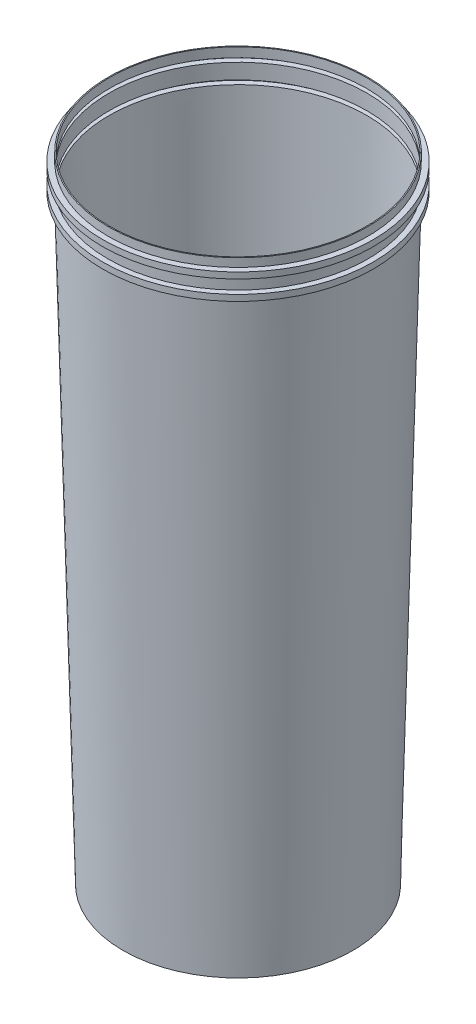
SolidWorks part; units mm, degrees
material "PVC Rigid"
ref_plane "Front Plane" through (0, 0, 0) normal (0, 0, 1) x (1, 0, 0)
ref_plane "Top Plane" through (0, 0, 0) normal (0, 1, 0) x (1, 0, 0)
ref_plane "Right Plane" through (0, 0, 0) normal (1, 0, 0) x (0, 0, -1)
sketch "Sketch1" plane through (0, 0, 0) normal (0, 0, 1) x (1, 0, 0)
  line L0 (0, 620) -> (-126, 620)
  line L11 (0, 0) -> (0, 620)
  line L12 (-126, 620) -> (-126, 610.7636)
  line L13 (-126, 610.7636) -> (-131.4225, 610.7636)
  line L14 (-131.4225, 610.7636) -> (-131.4225, 606.7636)
  line L15 (-131.4225, 606.7636) -> (-126.2576, 606.7636)
  line L16 (-126.2576, 606.7636) -> (-126.2576, 591.7636)
  line L17 (-126.2576, 591.7636) -> (-131.4225, 591.7636)
  line L18 (-131.4225, 591.7636) -> (-131.4225, 587.7636)
  line L19 (-131.4225, 587.7636) -> (-126.2576, 587.7636)
  line L20 (-126.2576, 587.7636) -> (-111.6099, 0)
  line L21 (-111.6099, 0) -> (0, 0)
  dimension "D6" = 620
revolve "Revolve1" add sketch "Sketch1" angle 360 about L11
shell "Shell4" [suppressed] thickness 1
shell "Shell5" thickness 1
sketch "Sketch2" [suppressed] plane through (0, 621, 0) normal (0, 1, 0) x (1, 0, 0)
  circle A0 centre (78.2296, 0) radius 15
  dimension "D1" = 30
extrude "Cut-Extrude1" [suppressed] cut sketch "Sketch2" against normal up to next
sketch "Sketch3" [suppressed] plane through (0, 621, 0) normal (0, 1, 0) x (1, 0, 0)
  circle A0 centre (0, 0) radius 4.4064
extrude "Boss-Extrude1" [suppressed] add sketch "Sketch3" along normal blind 80
fillet "Fillet1" [suppressed] radius 5
sketch "Sketch4" plane through (0, 0, 0) normal (0, 0, -1) x (1, 0, 0)
  line L0 (-14.9998, 0) -> (-14.9998, -280.0735)
  line L1 (14.9998, -280.0735) -> (14.9998, -0.0733)
  line L2 (-111.6099, 0) -> (111.6099, 0) construction
  arc A0 (-14.9998, -280.0735) -> (14.9998, -280.0735) centre (0, -280.0735) ccw
  dimension "D1" = 15
  dimension "D2" = 295
sweep "Sweep1" add path "Sketch4" circular profile diameter 5 parameters "D3"=5
sketch "Sketch5" [suppressed] plane through (0, 620, 0) normal (0, -1, 0) x (1, 0, 0)
  line L1 (-19.5, 9.5) -> (19.5, 9.5)
  line L2 (-19.5, 9.5) -> (-19.5, -9.5)
  line L3 (-19.5, -9.5) -> (19.5, -9.5)
  line L4 (19.5, 9.5) -> (19.5, -9.5)
  line L5 (0, -9.5) -> (0, 9.5) construction
  line L6 (-19.5, 0) -> (19.5, 0) construction
  line L7 (-17.5, 7.5) -> (17.5, 7.5)
  line L8 (-17.5, 7.5) -> (-17.5, -7.5)
  line L9 (-17.5, -7.5) -> (17.5, -7.5)
  line L10 (17.5, 7.5) -> (17.5, -7.5)
  line L11 (0, -7.5) -> (0, 7.5) construction
  line L12 (-17.5, 0) -> (17.5, 0) construction
  point P0 (0, 0)
  point P4 (0, 0)
  dimension "D1" = 35
  dimension "D2" = 15
  dimension "D3" = 2
  dimension "D4" = 2
extrude "Boss-Extrude2" [suppressed] add sketch "Sketch5" along normal up to surface (620 mm away) separate body
sketch "Sketch6" [suppressed] plane through (0, 621, 0) normal (0, 1, 0) x (1, 0, 0)
  circle A3 centre (78.2296, 0) radius 15 construction
  circle A4 centre (78.2296, 0) radius 15
extrude "Extrude-Thin1" [suppressed] add sketch "Sketch6" along normal blind 30 thin
thread "Thread1" [suppressed] pitch 4 start angle 0, offset 0, length 30, pitch 4, diameter 30
ref_plane "Plane1" through (93.2296, 621, 0) normal (0, 0, 1) x (1, 0, 0)
sketch "Thread Profile1" plane through (93.2296, 621, 0) normal (0, 0, 1) x (1, 0, 0)
  line L0 (0, 0) -> (0, 4) construction
  line L1 (0, 0) -> (2.1651, 1.25)
  line L2 (2.1651, 1.25) -> (2.1651, 1.75)
  line L3 (2.1651, 1.75) -> (0, 3)
  line L4 (2.1651, 1.5) -> (0, 1.5) construction
  line L11 (0, 0) -> (0, 3)
  point P2 (0, 0)
  dimension "Pitch" = 4
  dimension "Profile_Angle" = 60
  dimension "Profile_Land" = 0.5
  dimension "Profile_Height" = 2.1651
sketch "Sketch7" [suppressed] plane through (14.784, 0, 9.5) normal (0, 0, -1) x (-1, 0, 0)
  line L1 (14.784, 615.2271) -> (14.784, 417.1518) construction
  circle A0 centre (-17.7252, 599.4078) radius 5.7773
  circle A1 centre (14.784, 599.4078) radius 5.7773
  circle A2 centre (47.2932, 599.4078) radius 5.7773
extrude "Cut-Extrude2" [suppressed] cut sketch "Sketch7" against normal through all
